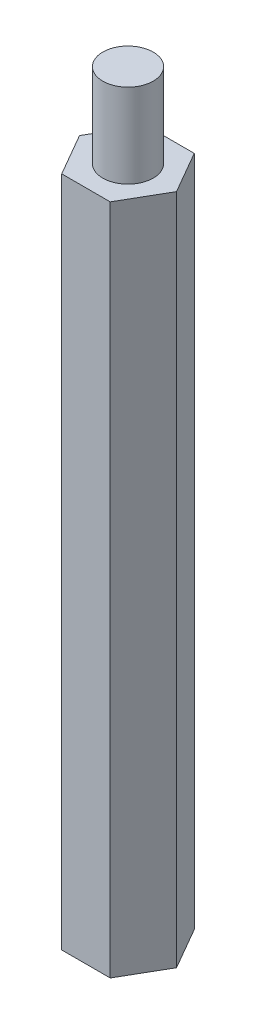
SolidWorks part; units mm, degrees
ref_plane "정면" through (0, 0, 0) normal (0, 0, 1) x (1, 0, 0)
ref_plane "윗면" through (0, 0, 0) normal (0, 1, 0) x (1, 0, 0)
ref_plane "우측면" through (0, 0, 0) normal (1, 0, 0) x (0, 0, -1)
sketch "스케치1" plane through (0, 0, 0) normal (0, 1, 0) x (1, 0, 0)
  line L1 (-1.4434, -2.5) -> (1.4434, -2.5)
  line L2 (1.4434, -2.5) -> (2.8868, 0)
  line L3 (2.8868, 0) -> (1.4434, 2.5)
  line L4 (1.4434, 2.5) -> (-1.4434, 2.5)
  line L5 (-1.4434, 2.5) -> (-2.8868, 0)
  line L6 (-2.8868, 0) -> (-1.4434, -2.5)
  circle A0 centre (0, 0) radius 2.5 construction
  dimension "D1" = 5
extrude "보스-돌출1" add sketch "스케치1" along normal blind 40
sketch "스케치2" plane through (0, 40, 0) normal (0, 1, 0) x (1, 0, 0)
  circle A0 centre (0, 0) radius 1.5
  dimension "D1" = 3
extrude "보스-돌출2" add sketch "스케치2" along normal blind 5
sketch "스케치3" plane through (0, 0, 0) normal (0, -1, 0) x (1, 0, 0)
  circle A0 centre (0, 0) radius 1.5
  dimension "D1" = 3
extrude "컷-돌출1" cut sketch "스케치3" against normal blind 6
